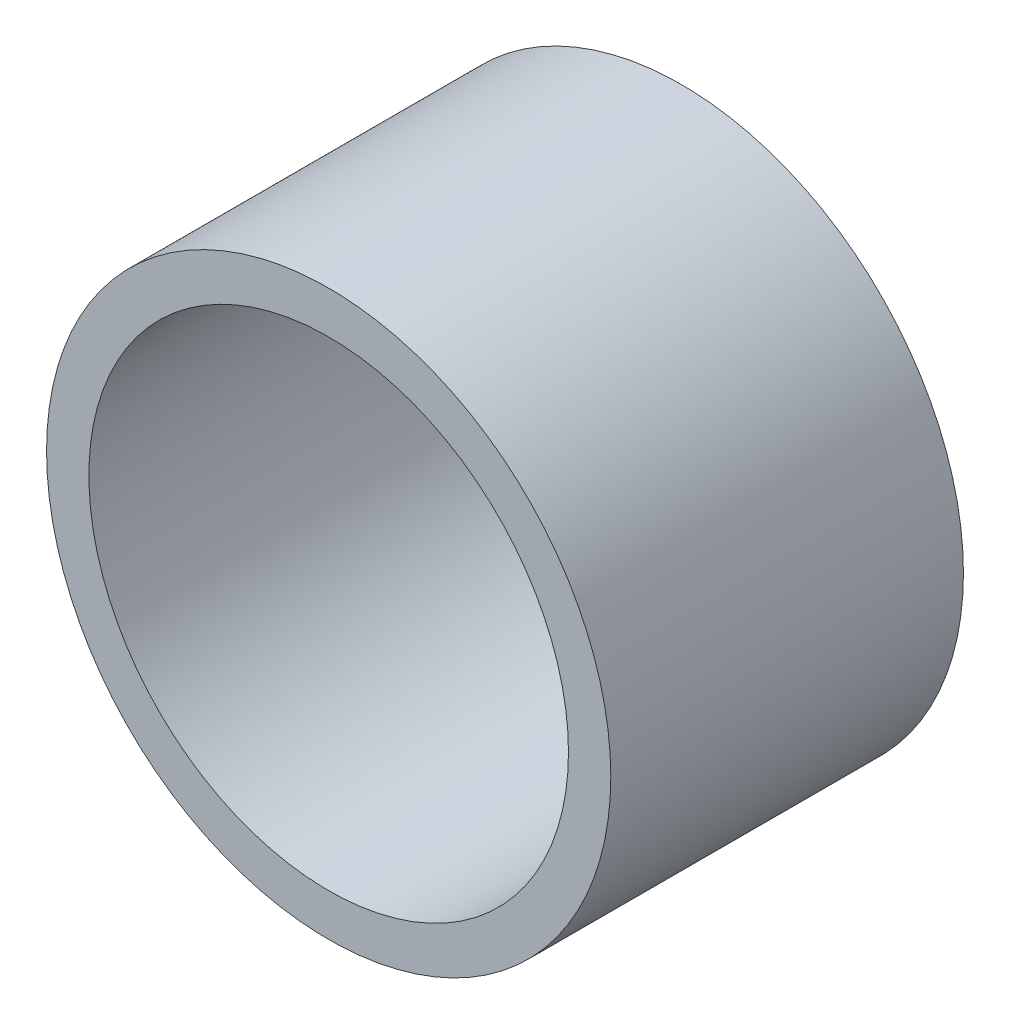
SolidWorks part; units mm, degrees
ref_plane "Front Plane" through (0, 0, 0) normal (0, 0, 1) x (1, 0, 0)
ref_plane "Top Plane" through (0, 0, 0) normal (0, 1, 0) x (1, 0, 0)
ref_plane "Right Plane" through (0, 0, 0) normal (1, 0, 0) x (0, 0, -1)
sketch "Sketch1" plane through (0, 0, 0) normal (0, 0, 1) x (1, 0, 0)
  circle A0 centre (0, 0) radius 5.1
  circle A1 centre (0, 0) radius 6
  dimension "D1" = 10.2
  dimension "D2" = 12
extrude "Boss-Extrude1" add sketch "Sketch1" along normal blind 7.5
